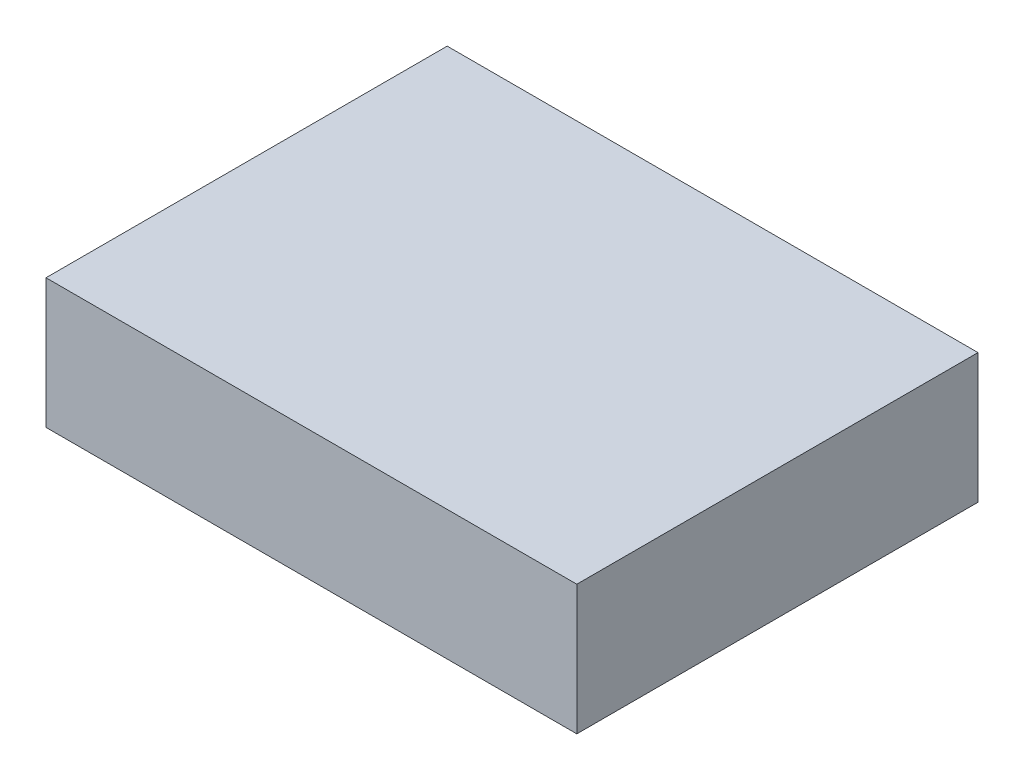
SolidWorks part; units mm, degrees
ref_plane "前视基准面" through (0, 0, 0) normal (0, 0, 1) x (1, 0, 0)
ref_plane "上视基准面" through (0, 0, 0) normal (0, 1, 0) x (1, 0, 0)
ref_plane "右视基准面" through (0, 0, 0) normal (1, 0, 0) x (0, 0, -1)
sketch "草图1" plane through (0, 0, 0) normal (0, 1, 0) x (1, 0, 0)
  line L1 (-43, 32.5) -> (43, 32.5)
  line L2 (-43, 32.5) -> (-43, -32.5)
  line L3 (-43, -32.5) -> (43, -32.5)
  line L4 (43, 32.5) -> (43, -32.5)
  line L5 (-43, 32.5) -> (43, -32.5) construction
  line L6 (-43, -32.5) -> (43, 32.5) construction
  point P0 (0, 0)
  dimension "D1" = 65
  dimension "D2" = 86
extrude "凸台-拉伸1" add sketch "草图1" along normal blind 21
